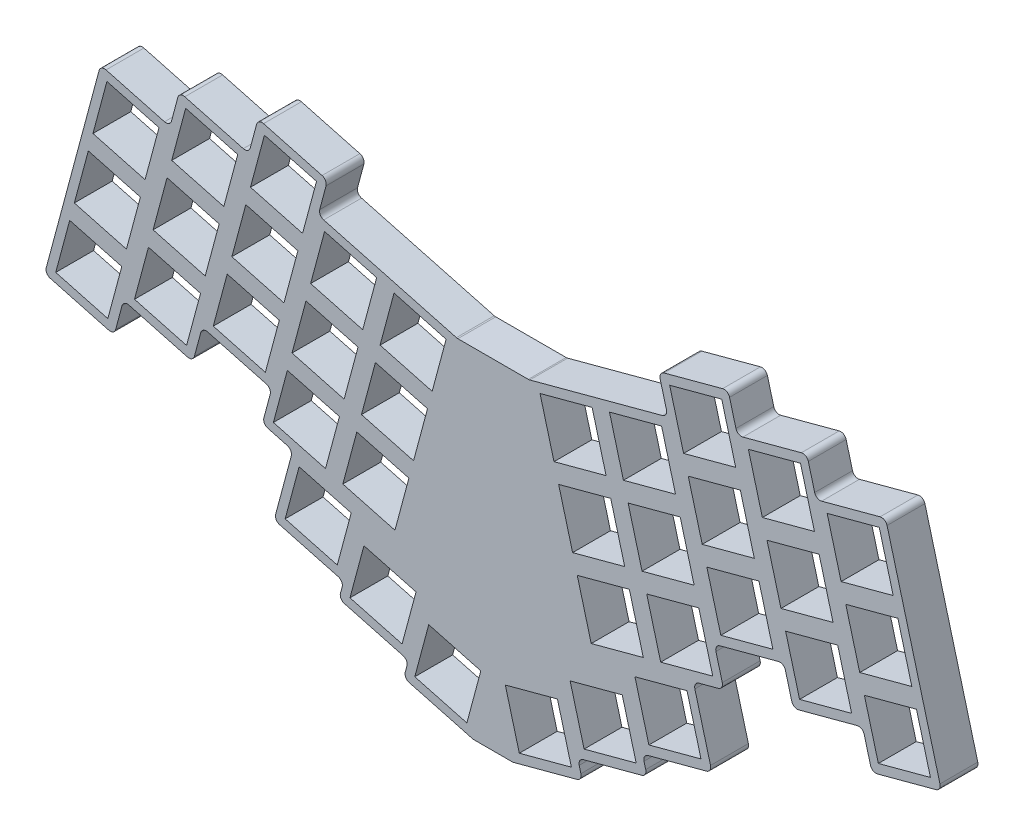
SolidWorks part; units mm, degrees
ref_plane "Front Plane" through (0, 0, 0) normal (0, 0, 1) x (1, 0, 0)
ref_plane "Top Plane" through (0, 0, 0) normal (0, 1, 0) x (1, 0, 0)
ref_plane "Right Plane" through (0, 0, 0) normal (1, 0, 0) x (0, 0, -1)
sketch "Sketch2" plane through (0, 0, 0) normal (0, 0, 1) x (1, 0, 0)
  line L24 (-91.0661, -19.9437) -> (-94.7543, -33.7081)
  line L25 (-77.3017, -23.6319) -> (-91.0661, -19.9437)
  line L26 (-80.9898, -37.3963) -> (-77.3017, -23.6319)
  line L27 (-94.7543, -33.7081) -> (-80.9898, -37.3963)
  line L32 (-81.231, 16.7615) -> (-84.9192, 2.997)
  line L33 (-67.4665, 13.0733) -> (-81.231, 16.7615)
  line L34 (-71.1547, -0.6911) -> (-67.4665, 13.0733)
  line L35 (-84.9192, 2.997) -> (-71.1547, -0.6911)
  line L40 (-86.1485, -1.5911) -> (-89.8367, -15.3556)
  line L41 (-72.3841, -5.2793) -> (-86.1485, -1.5911)
  line L42 (-76.0723, -19.0437) -> (-72.3841, -5.2793)
  line L43 (-89.8367, -15.3556) -> (-76.0723, -19.0437)
  line L48 (-65.3372, 2.6676) -> (-69.0253, -11.0968)
  line L49 (-51.5727, -1.0206) -> (-65.3372, 2.6676)
  line L50 (-55.2609, -14.785) -> (-51.5727, -1.0206)
  line L51 (-69.0253, -11.0968) -> (-55.2609, -14.785)
  line L56 (-60.4196, 21.0202) -> (-64.1078, 7.2558)
  line L57 (-46.6552, 17.332) -> (-60.4196, 21.0202)
  line L58 (-50.3433, 3.5676) -> (-46.6552, 17.332)
  line L59 (-64.1078, 7.2558) -> (-50.3433, 3.5676)
  line L64 (-70.2547, -15.685) -> (-73.9429, -29.4494)
  line L65 (-56.4903, -19.3731) -> (-70.2547, -15.685)
  line L66 (-60.1785, -33.1376) -> (-56.4903, -19.3731)
  line L67 (-73.9429, -29.4494) -> (-60.1785, -33.1376)
  line L72 (-3.2384, -72.9824) -> (-17.0028, -69.2943)
  line L73 (-6.9266, -86.7469) -> (-3.2384, -72.9824)
  line L74 (-20.691, -83.0587) -> (-6.9266, -86.7469)
  line L75 (-17.0028, -69.2943) -> (-20.691, -83.0587)
  line L80 (-20.3616, -63.4767) -> (-34.126, -59.7886)
  line L81 (-24.0498, -77.2412) -> (-20.3616, -63.4767)
  line L82 (-37.8142, -73.553) -> (-24.0498, -77.2412)
  line L83 (-34.126, -59.7886) -> (-37.8142, -73.553)
  line L88 (-54.3609, -29.7788) -> (-58.0491, -43.5433)
  line L89 (-40.5965, -33.467) -> (-54.3609, -29.7788)
  line L90 (-44.2847, -47.2314) -> (-40.5965, -33.467)
  line L91 (-58.0491, -43.5433) -> (-44.2847, -47.2314)
  line L96 (-31.0908, -16.3438) -> (-34.7789, -30.1082)
  line L97 (-17.3263, -20.032) -> (-31.0908, -16.3438)
  line L98 (-21.0145, -33.7964) -> (-17.3263, -20.032)
  line L99 (-34.7789, -30.1082) -> (-21.0145, -33.7964)
  line L104 (-44.5258, 6.9264) -> (-48.214, -6.8381)
  line L105 (-30.7614, 3.2382) -> (-44.5258, 6.9264)
  line L106 (-34.4495, -10.5263) -> (-30.7614, 3.2382)
  line L107 (-48.214, -6.8381) -> (-34.4495, -10.5263)
  line L112 (-51.2492, -50.2829) -> (-54.9374, -64.0473)
  line L113 (-37.4848, -53.971) -> (-51.2492, -50.2829)
  line L114 (-41.173, -67.7355) -> (-37.4848, -53.971)
  line L115 (-54.9374, -64.0473) -> (-41.173, -67.7355)
  line L120 (-26.1732, 2.0088) -> (-29.8614, -11.7557)
  line L121 (-12.4088, -1.6794) -> (-26.1732, 2.0088)
  line L122 (-16.0969, -15.4438) -> (-12.4088, -1.6794)
  line L123 (-29.8614, -11.7557) -> (-16.0969, -15.4438)
  line L128 (-49.4434, -11.4262) -> (-53.1315, -25.1907)
  line L129 (-35.6789, -15.1144) -> (-49.4434, -11.4262)
  line L130 (-39.3671, -28.8789) -> (-35.6789, -15.1144)
  line L131 (-53.1315, -25.1907) -> (-39.3671, -28.8789)
  line L136 (-36.0083, -34.6964) -> (-39.6965, -48.4608)
  line L137 (-22.2439, -38.3846) -> (-36.0083, -34.6964)
  line L138 (-25.9321, -52.149) -> (-22.2439, -38.3846)
  line L139 (-39.6965, -48.4608) -> (-25.9321, -52.149)
  line L160 (-105.7305, -1.2617) -> (-91.9661, -4.9499)
  line L161 (-102.0424, 12.5027) -> (-105.7305, -1.2617)
  line L162 (-88.2779, 8.8146) -> (-102.0424, 12.5027)
  line L163 (-91.9661, -4.9499) -> (-88.2779, 8.8146)
  line L168 (-110.6481, -19.6143) -> (-96.8836, -23.3025)
  line L169 (-106.9599, -5.8498) -> (-110.6481, -19.6143)
  line L170 (-93.1955, -9.538) -> (-106.9599, -5.8498)
  line L171 (-96.8836, -23.3025) -> (-93.1955, -9.538)
  line L176 (-115.5657, -37.9669) -> (-101.8012, -41.6551)
  line L177 (-111.8775, -24.2024) -> (-115.5657, -37.9669)
  line L178 (-98.113, -27.8906) -> (-111.8775, -24.2024)
  line L179 (-101.8012, -41.6551) -> (-98.113, -27.8906)
  line L184 (94.7543, -33.7081) -> (91.0661, -19.9437)
  line L185 (80.9898, -37.3963) -> (94.7543, -33.7081)
  line L186 (77.3017, -23.6319) -> (80.9898, -37.3963)
  line L187 (91.0661, -19.9437) -> (77.3017, -23.6319)
  line L192 (84.9192, 2.997) -> (81.231, 16.7615)
  line L193 (71.1547, -0.6911) -> (84.9192, 2.997)
  line L194 (67.4665, 13.0733) -> (71.1547, -0.6911)
  line L195 (81.231, 16.7615) -> (67.4665, 13.0733)
  line L200 (89.8367, -15.3556) -> (86.1485, -1.5911)
  line L201 (76.0723, -19.0437) -> (89.8367, -15.3556)
  line L202 (72.3841, -5.2793) -> (76.0723, -19.0437)
  line L203 (86.1485, -1.5911) -> (72.3841, -5.2793)
  line L208 (69.0253, -11.0968) -> (65.3372, 2.6676)
  line L209 (55.2609, -14.785) -> (69.0253, -11.0968)
  line L210 (51.5727, -1.0206) -> (55.2609, -14.785)
  line L211 (65.3372, 2.6676) -> (51.5727, -1.0206)
  line L216 (64.1078, 7.2558) -> (60.4196, 21.0202)
  line L217 (50.3433, 3.5676) -> (64.1078, 7.2558)
  line L218 (46.6552, 17.332) -> (50.3433, 3.5676)
  line L219 (60.4196, 21.0202) -> (46.6552, 17.332)
  line L224 (73.9429, -29.4494) -> (70.2547, -15.685)
  line L225 (60.1785, -33.1376) -> (73.9429, -29.4494)
  line L226 (56.4903, -19.3731) -> (60.1785, -33.1376)
  line L227 (70.2547, -15.685) -> (56.4903, -19.3731)
  line L232 (17.0028, -69.2943) -> (3.2384, -72.9824)
  line L233 (20.691, -83.0587) -> (17.0028, -69.2943)
  line L234 (6.9266, -86.7469) -> (20.691, -83.0587)
  line L235 (3.2384, -72.9824) -> (6.9266, -86.7469)
  line L240 (34.126, -59.7886) -> (20.3616, -63.4767)
  line L241 (37.8142, -73.553) -> (34.126, -59.7886)
  line L242 (24.0498, -77.2412) -> (37.8142, -73.553)
  line L243 (20.3616, -63.4767) -> (24.0498, -77.2412)
  line L248 (58.0491, -43.5433) -> (54.3609, -29.7788)
  line L249 (44.2847, -47.2314) -> (58.0491, -43.5433)
  line L250 (40.5965, -33.467) -> (44.2847, -47.2314)
  line L251 (54.3609, -29.7788) -> (40.5965, -33.467)
  line L256 (34.7789, -30.1082) -> (31.0908, -16.3438)
  line L257 (21.0145, -33.7964) -> (34.7789, -30.1082)
  line L258 (17.3263, -20.032) -> (21.0145, -33.7964)
  line L259 (31.0908, -16.3438) -> (17.3263, -20.032)
  line L264 (48.214, -6.8381) -> (44.5258, 6.9264)
  line L265 (34.4495, -10.5263) -> (48.214, -6.8381)
  line L266 (30.7614, 3.2382) -> (34.4495, -10.5263)
  line L267 (44.5258, 6.9264) -> (30.7614, 3.2382)
  line L272 (54.9374, -64.0473) -> (51.2492, -50.2829)
  line L273 (41.173, -67.7355) -> (54.9374, -64.0473)
  line L274 (37.4848, -53.971) -> (41.173, -67.7355)
  line L275 (51.2492, -50.2829) -> (37.4848, -53.971)
  line L280 (29.8614, -11.7557) -> (26.1732, 2.0088)
  line L281 (16.0969, -15.4438) -> (29.8614, -11.7557)
  line L282 (12.4088, -1.6794) -> (16.0969, -15.4438)
  line L283 (26.1732, 2.0088) -> (12.4088, -1.6794)
  line L288 (53.1315, -25.1907) -> (49.4434, -11.4262)
  line L289 (39.3671, -28.8789) -> (53.1315, -25.1907)
  line L290 (35.6789, -15.1144) -> (39.3671, -28.8789)
  line L291 (49.4434, -11.4262) -> (35.6789, -15.1144)
  line L296 (39.6965, -48.4608) -> (36.0083, -34.6964)
  line L297 (25.9321, -52.149) -> (39.6965, -48.4608)
  line L298 (22.2439, -38.3846) -> (25.9321, -52.149)
  line L299 (36.0083, -34.6964) -> (22.2439, -38.3846)
  line L304 (91.9661, -4.9499) -> (105.7305, -1.2617)
  line L305 (88.2779, 8.8146) -> (91.9661, -4.9499)
  line L306 (102.0424, 12.5027) -> (88.2779, 8.8146)
  line L307 (105.7305, -1.2617) -> (102.0424, 12.5027)
  line L312 (96.8836, -23.3025) -> (110.6481, -19.6143)
  line L313 (93.1955, -9.538) -> (96.8836, -23.3025)
  line L314 (106.9599, -5.8498) -> (93.1955, -9.538)
  line L315 (110.6481, -19.6143) -> (106.9599, -5.8498)
  line L320 (101.8012, -41.6551) -> (115.5657, -37.9669)
  line L321 (98.113, -27.8906) -> (101.8012, -41.6551)
  line L322 (111.8775, -24.2024) -> (98.113, -27.8906)
  line L323 (115.5657, -37.9669) -> (111.8775, -24.2024)
  line L408 (9.3025, 0) -> (-9.3025, 0)
  line L409 (-9.6907, 0.0511) -> (-44.7563, 9.4469)
  line L410 (-45.817, 11.284) -> (-44.1346, 17.5625)
  line L411 (-45.1953, 19.3996) -> (-60.6501, 23.5408)
  line L412 (-62.4872, 22.4801) -> (-64.1695, 16.2016)
  line L413 (-66.0067, 15.1409) -> (-81.4615, 19.282)
  line L414 (-83.2986, 18.2214) -> (-84.9809, 11.9428)
  line L415 (-86.818, 10.8822) -> (-102.2728, 15.0233)
  line L416 (-104.11, 13.9626) -> (-118.0862, -38.1974)
  line L417 (-117.0255, -40.0345) -> (-101.5707, -44.1756)
  line L418 (-99.7336, -43.1149) -> (-98.0513, -36.8364)
  line L419 (-96.2142, -35.7758) -> (-80.7593, -39.9169)
  line L420 (-78.9222, -38.8562) -> (-77.2399, -32.5777)
  line L421 (-75.4028, -31.517) -> (-59.948, -35.6581)
  line L422 (-58.8873, -37.4952) -> (-60.5696, -43.7738)
  line L423 (-59.509, -45.6109) -> (-54.3775, -46.9859)
  line L424 (-53.3168, -48.823) -> (-57.4579, -64.2778)
  line L425 (-56.3973, -66.1149) -> (-40.9425, -70.256)
  line L426 (-39.8818, -72.0931) -> (-40.3347, -73.7835)
  line L427 (-39.2741, -75.6206) -> (-23.8193, -79.7617)
  line L428 (-22.7586, -81.5988) -> (-23.2115, -83.2892)
  line L429 (-22.1509, -85.1263) -> (-5.4379, -89.6045)
  line L430 (-5.0497, -89.6557) -> (5.0497, -89.6557)
  line L431 (5.4379, -89.6045) -> (22.1509, -85.1263)
  line L432 (23.2115, -83.2892) -> (22.7586, -81.5988)
  line L433 (23.8193, -79.7617) -> (39.2741, -75.6206)
  line L434 (40.3347, -73.7835) -> (39.8818, -72.0931)
  line L435 (40.9425, -70.256) -> (56.3973, -66.1149)
  line L436 (57.4579, -64.2778) -> (53.3168, -48.823)
  line L437 (54.3775, -46.9859) -> (59.509, -45.6109)
  line L438 (60.5696, -43.7738) -> (58.8873, -37.4952)
  line L439 (59.948, -35.6581) -> (75.4028, -31.517)
  line L440 (77.2399, -32.5777) -> (78.9222, -38.8562)
  line L441 (80.7593, -39.9169) -> (96.2142, -35.7758)
  line L442 (98.0513, -36.8364) -> (99.7336, -43.1149)
  line L443 (101.5707, -44.1756) -> (117.0255, -40.0345)
  line L444 (118.0862, -38.1974) -> (104.11, 13.9626)
  line L445 (102.2728, 15.0233) -> (86.818, 10.8822)
  line L446 (84.9809, 11.9428) -> (83.2986, 18.2214)
  line L447 (81.4615, 19.282) -> (66.0067, 15.1409)
  line L448 (64.1695, 16.2016) -> (62.4872, 22.4801)
  line L449 (60.6501, 23.5408) -> (45.1953, 19.3996)
  line L450 (44.1346, 17.5625) -> (45.817, 11.284)
  line L451 (44.7563, 9.4469) -> (9.6907, 0.0511)
  arc A104 (9.3025, 0) -> (9.6907, 0.0511) centre (9.3025, 1.5) ccw
  arc A105 (-9.6907, 0.0511) -> (-9.3025, 0) centre (-9.3025, 1.5) ccw
  arc A106 (-45.817, 11.284) -> (-44.7563, 9.4469) centre (-44.3681, 10.8958) ccw
  arc A107 (-44.1346, 17.5625) -> (-45.1953, 19.3996) centre (-45.5835, 17.9508) ccw
  arc A108 (-60.6501, 23.5408) -> (-62.4872, 22.4801) centre (-61.0383, 22.0919) ccw
  arc A109 (-66.0067, 15.1409) -> (-64.1695, 16.2016) centre (-65.6184, 16.5898) ccw
  arc A110 (-81.4615, 19.282) -> (-83.2986, 18.2214) centre (-81.8497, 17.8331) ccw
  arc A111 (-86.818, 10.8822) -> (-84.9809, 11.9428) centre (-86.4298, 12.3311) ccw
  arc A112 (-102.2728, 15.0233) -> (-104.11, 13.9626) centre (-102.6611, 13.5744) ccw
  arc A113 (-118.0862, -38.1974) -> (-117.0255, -40.0345) centre (-116.6373, -38.5856) ccw
  arc A114 (-101.5707, -44.1756) -> (-99.7336, -43.1149) centre (-101.1825, -42.7267) ccw
  arc A115 (-96.2142, -35.7758) -> (-98.0513, -36.8364) centre (-96.6024, -37.2246) ccw
  arc A116 (-80.7593, -39.9169) -> (-78.9222, -38.8562) centre (-80.3711, -38.468) ccw
  arc A117 (-75.4028, -31.517) -> (-77.2399, -32.5777) centre (-75.791, -32.9659) ccw
  arc A118 (-58.8873, -37.4952) -> (-59.948, -35.6581) centre (-60.3362, -37.107) ccw
  arc A119 (-60.5696, -43.7738) -> (-59.509, -45.6109) centre (-59.1207, -44.162) ccw
  arc A120 (-53.3168, -48.823) -> (-54.3775, -46.9859) centre (-54.7657, -48.4347) ccw
  arc A121 (-57.4579, -64.2778) -> (-56.3973, -66.1149) centre (-56.0091, -64.666) ccw
  arc A122 (-39.8818, -72.0931) -> (-40.9425, -70.256) centre (-41.3307, -71.7049) ccw
  arc A123 (-40.3347, -73.7835) -> (-39.2741, -75.6206) centre (-38.8859, -74.1717) ccw
  arc A124 (-22.7586, -81.5988) -> (-23.8193, -79.7617) centre (-24.2075, -81.2106) ccw
  arc A125 (-23.2115, -83.2892) -> (-22.1509, -85.1263) centre (-21.7627, -83.6774) ccw
  arc A126 (-5.4379, -89.6045) -> (-5.0497, -89.6557) centre (-5.0497, -88.1557) ccw
  arc A127 (5.0497, -89.6557) -> (5.4379, -89.6045) centre (5.0497, -88.1557) ccw
  arc A128 (22.1509, -85.1263) -> (23.2115, -83.2892) centre (21.7627, -83.6774) ccw
  arc A129 (23.8193, -79.7617) -> (22.7586, -81.5988) centre (24.2075, -81.2106) ccw
  arc A130 (39.2741, -75.6206) -> (40.3347, -73.7835) centre (38.8859, -74.1717) ccw
  arc A131 (40.9425, -70.256) -> (39.8818, -72.0931) centre (41.3307, -71.7049) ccw
  arc A132 (56.3973, -66.1149) -> (57.4579, -64.2778) centre (56.0091, -64.666) ccw
  arc A133 (54.3775, -46.9859) -> (53.3168, -48.823) centre (54.7657, -48.4347) ccw
  arc A134 (59.509, -45.6109) -> (60.5696, -43.7738) centre (59.1207, -44.162) ccw
  arc A135 (59.948, -35.6581) -> (58.8873, -37.4952) centre (60.3362, -37.107) ccw
  arc A136 (77.2399, -32.5777) -> (75.4028, -31.517) centre (75.791, -32.9659) ccw
  arc A137 (78.9222, -38.8562) -> (80.7593, -39.9169) centre (80.3711, -38.468) ccw
  arc A138 (98.0513, -36.8364) -> (96.2142, -35.7758) centre (96.6024, -37.2246) ccw
  arc A139 (99.7336, -43.1149) -> (101.5707, -44.1756) centre (101.1825, -42.7267) ccw
  arc A140 (117.0255, -40.0345) -> (118.0862, -38.1974) centre (116.6373, -38.5856) ccw
  arc A141 (104.11, 13.9626) -> (102.2728, 15.0233) centre (102.6611, 13.5744) ccw
  arc A142 (84.9809, 11.9428) -> (86.818, 10.8822) centre (86.4298, 12.3311) ccw
  arc A143 (83.2986, 18.2214) -> (81.4615, 19.282) centre (81.8497, 17.8331) ccw
  arc A144 (64.1695, 16.2016) -> (66.0067, 15.1409) centre (65.6184, 16.5898) ccw
  arc A145 (62.4872, 22.4801) -> (60.6501, 23.5408) centre (61.0383, 22.0919) ccw
  arc A146 (45.1953, 19.3996) -> (44.1346, 17.5625) centre (45.5835, 17.9508) ccw
  arc A147 (44.7563, 9.4469) -> (45.817, 11.284) centre (44.3681, 10.8958) ccw
extrude "Boss-Extrude1" add sketch "Sketch2" along normal blind 10
sketch "Sketch3" plane through (0, 0, 0) normal (0, 0, -1) x (-1, 0, 0)
  line L0 (-103.7394, 15.4421) -> (-85.3385, 10.5116)
  line L1 (-85.3385, 10.5116) -> (-90.269, -7.8893)
  line L2 (-90.269, -7.8893) -> (-108.6699, -2.9588)
  line L3 (-103.7394, 15.4421) -> (-108.6699, -2.9588)
  line L4 (-105.7305, -1.2617) -> (-102.0424, 12.5027) construction
  line L5 (-20.691, -83.0587) -> (-6.9266, -86.7469)
  line L6 (-102.0424, 12.5027) -> (-88.2779, 8.8146) construction
  line L7 (-108.6699, -2.9588) -> (-90.269, -7.8893)
  line L8 (-90.269, -7.8893) -> (-95.1995, -26.2901)
  line L9 (-95.1995, -26.2901) -> (-113.6004, -21.3596)
  line L10 (-108.6699, -2.9588) -> (-113.6004, -21.3596)
  line L11 (-113.6004, -21.3596) -> (-95.1995, -26.2901)
  line L12 (-95.1995, -26.2901) -> (-100.13, -44.691)
  line L13 (-100.13, -44.691) -> (-118.5309, -39.7605)
  line L14 (-113.6004, -21.3596) -> (-118.5309, -39.7605)
  line L16 (6.9266, -86.7469) -> (20.691, -83.0587)
  dimension "D1" = 19.05
  dimension "D2" = 19.05
  dimension "D3" = 19.05
  dimension "D4" = 2.4
  dimension "D5" = 2.4
  dimension "D6" = 3
